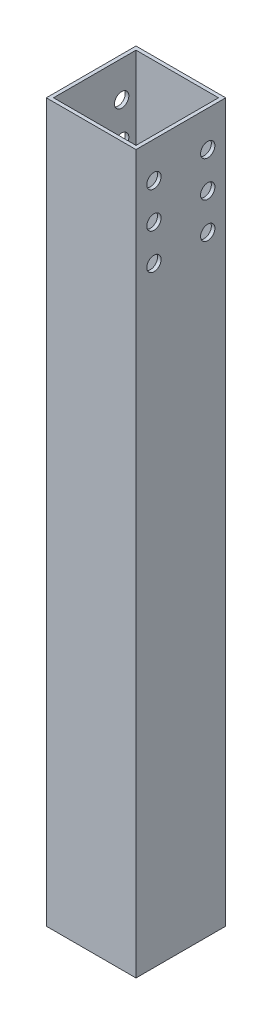
SolidWorks part; units mm, degrees
material "1060 Alloy"
ref_plane "Front Plane" through (0, 0, 0) normal (0, 0, 1) x (1, 0, 0)
ref_plane "Top Plane" through (0, 0, 0) normal (0, 1, 0) x (1, 0, 0)
ref_plane "Right Plane" through (0, 0, 0) normal (1, 0, 0) x (0, 0, -1)
sketch "Sketch1" plane through (0, 0, 0) normal (0, 1, 0) x (1, 0, 0)
  line L0 (-11.5, -11.5) -> (11.5, -11.5)
  line L1 (-12.5, 12.5) -> (12.5, 12.5)
  line L2 (-12.5, 12.5) -> (-12.5, -12.5)
  line L3 (-12.5, -12.5) -> (12.5, -12.5)
  line L4 (12.5, 12.5) -> (12.5, -12.5)
  line L5 (-12.5, 12.5) -> (12.5, -12.5) construction
  line L6 (-12.5, -12.5) -> (12.5, 12.5) construction
  line L7 (11.5, 11.5) -> (11.5, -11.5)
  line L8 (-11.5, 11.5) -> (11.5, 11.5)
  line L9 (-11.5, 11.5) -> (-11.5, -11.5)
  point P0 (0, 0)
  dimension "D1" = 25
  dimension "D2" = 25
  dimension "D3" = 1
extrude "Boss-Extrude1" add sketch "Sketch1" along normal blind 200
sketch "Sketch3" plane through (12.5, 0, 0) normal (1, 0, 0) x (0, 0, -1)
  line L0 (0, 0) -> (0, 288.1425) construction
  line L1 (-12.5, 200) -> (12.5, 200) construction
  circle A0 centre (7.5, 190) radius 2
  circle A1 centre (7.5, 180) radius 2
  circle A3 centre (-7.5, 190) radius 2
  circle A5 centre (-7.5, 180) radius 2
  circle A6 centre (7.5, 170) radius 2
  circle A7 centre (-7.5, 170) radius 2
  dimension "D1" = 7.5
  dimension "D5" = 10
  dimension "D11" = 7.5
  dimension "D2" = 7.5
  dimension "D3" = 7.5
  dimension "D4" = 7.5
  dimension "D6" = 7.5
  dimension "D7" = 10
  dimension "D8" = 10
  dimension "D9" = 10
  dimension "D10" = 10
  dimension "D12" = 10
extrude "Cut-Extrude1" cut sketch "Sketch3" against normal blind 25
